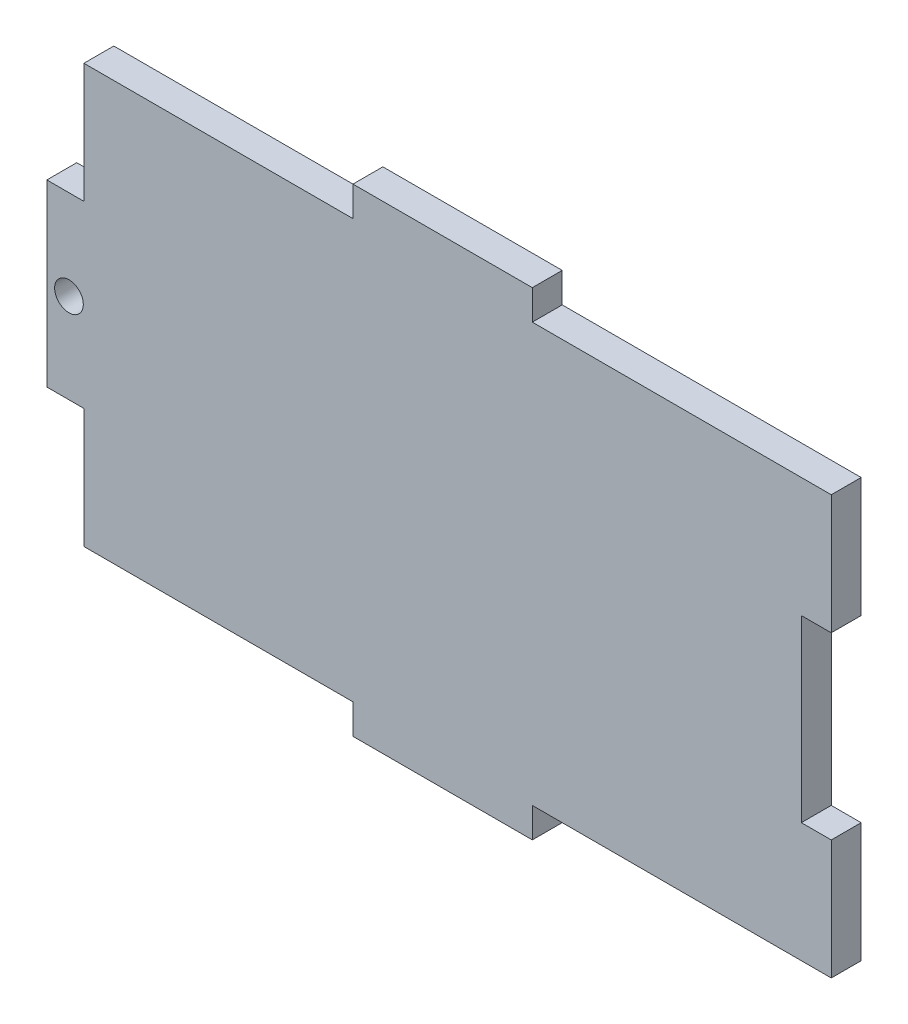
SolidWorks part; units mm, degrees
ref_plane "Front Plane" through (0, 0, 0) normal (0, 0, 1) x (1, 0, 0)
ref_plane "Top Plane" through (0, 0, 0) normal (0, 1, 0) x (1, 0, 0)
ref_plane "Right Plane" through (0, 0, 0) normal (1, 0, 0) x (0, 0, -1)
sketch "Sketch1" plane through (0, 0, 0) normal (0, 0, 1) x (1, 0, 0)
  line L1 (0, 0) -> (79.375, 0)
  line L2 (0, 0) -> (0, 44.45)
  line L3 (0, 44.45) -> (79.375, 44.45)
  line L4 (79.375, 0) -> (79.375, 44.45)
  dimension "D1" = 44.45
  dimension "D2" = 79.375
extrude "Boss-Extrude1" add sketch "Sketch1" along normal blind 3.175
sketch "Sketch2" plane through (0, 0, 3.175) normal (0, 0, 1) x (1, 0, 0)
  line L0 (0, -55) -> (0, 55) construction
  line L1 (0, 31.75) -> (-3.175, 31.75)
  line L2 (0, 31.75) -> (0, 12.7)
  line L3 (0, 12.7) -> (-3.175, 12.7)
  line L4 (-3.175, 31.75) -> (-3.175, 12.7)
  line L5 (79.375, 44.45) -> (0, 44.45) construction
  dimension "D1" = 3.175
  dimension "D2" = 19.05
  dimension "D3" = 12.7
extrude "Boss-Extrude2" add sketch "Sketch2" against normal blind 3.175
sketch "Sketch5" plane through (0, 0, 3.175) normal (0, 0, 1) x (1, 0, 0)
  line L0 (79.375, 44.45) -> (0, 44.45) construction
  line L1 (28.575, 44.45) -> (47.625, 44.45)
  line L2 (28.575, 44.45) -> (28.575, 47.625)
  line L3 (28.575, 47.625) -> (47.625, 47.625)
  line L4 (47.625, 44.45) -> (47.625, 47.625)
  line L6 (-3.175, 22.225) -> (79.375, 22.225) construction
  line L7 (47.625, 0) -> (47.625, -3.175)
  line L8 (28.575, -3.175) -> (47.625, -3.175)
  line L9 (28.575, 0) -> (28.575, -3.175)
  line L10 (28.575, 0) -> (47.625, 0)
  line L13 (-3.175, 31.75) -> (-3.175, 12.7) construction
  line L14 (79.375, 0) -> (79.375, 44.45) construction
  point P12 (38.1, 0)
  point P18 (38.1, 22.225)
  point P19 (38.1, 44.45)
  dimension "D1" = 19.05
  dimension "D2" = 3.175
extrude "Boss-Extrude3" add sketch "Sketch5" against normal blind 3.175
sketch "Sketch3" plane through (0, 0, 3.175) normal (0, 0, 1) x (1, 0, 0)
  line L0 (79.375, 0) -> (79.375, 44.45) construction
  line L1 (79.375, 12.7) -> (76.2, 12.7)
  line L2 (79.375, 12.7) -> (79.375, 31.75)
  line L3 (79.375, 31.75) -> (76.2, 31.75)
  line L4 (76.2, 12.7) -> (76.2, 31.75)
  line L5 (79.375, 44.45) -> (47.625, 44.45) construction
  dimension "D1" = 19.05
  dimension "D2" = 3.175
  dimension "D3" = 12.7
extrude "Cut-Extrude1" cut sketch "Sketch3" against normal blind 3.175
sketch "Sketch6" plane through (0, 0, 3.175) normal (0, 0, 1) x (1, 0, 0)
  line L0 (27.6489, 22.225) -> (39.7152, 22.225) construction
  line L1 (-3.937, 31.75) -> (-3.175, 31.75)
  line L2 (-3.937, 31.75) -> (-3.937, 12.7)
  line L3 (-3.937, 12.7) -> (-3.175, 12.7)
  line L4 (-3.175, 31.75) -> (-3.175, 12.7)
  line L5 (-3.937, 31.75) -> (-3.175, 12.7) construction
  line L6 (-3.937, 12.7) -> (-3.175, 31.75) construction
  line L7 (79.375, 44.45) -> (47.625, 44.45) construction
  line L8 (-3.175, 31.75) -> (-3.175, 12.7) construction
  point P0 (-3.556, 22.225)
  dimension "D1" = 22.225
  dimension "D2" = 0.762
  dimension "D3" = 19.05
extrude "Boss-Extrude4" add sketch "Sketch6" against normal blind 3.175
sketch "Sketch7" plane through (0, 0, 3.175) normal (0, 0, 1) x (1, 0, 0)
  line L0 (-1.5875, 31.75) -> (-1.5875, 12.7) construction
  line L3 (0, -1.7463) -> (0, 1.7463) construction
  circle A0 centre (-1.5875, 22.225) radius 1.524
  dimension "D1" = 3.048
  dimension "D2" = 1.5875
extrude "Cut-Extrude2" cut sketch "Sketch7" against normal through all
